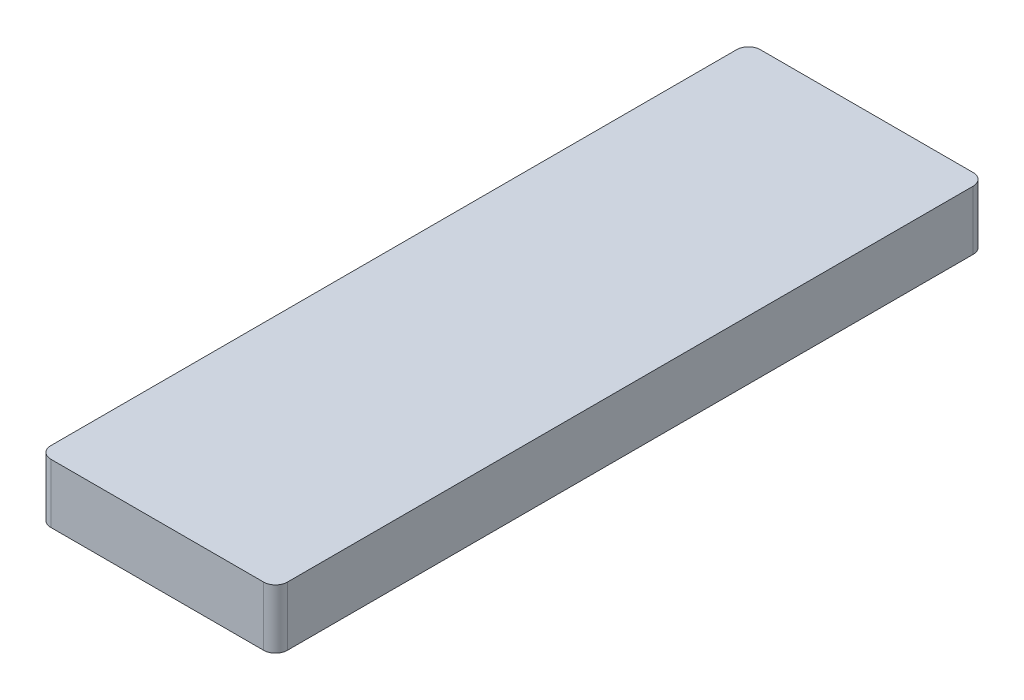
SolidWorks part; units mm, degrees
ref_plane "Front Plane" through (0, 0, 0) normal (0, 0, 1) x (1, 0, 0)
ref_plane "Top Plane" through (0, 0, 0) normal (0, 1, 0) x (1, 0, 0)
ref_plane "Right Plane" through (0, 0, 0) normal (1, 0, 0) x (0, 0, -1)
sketch "Sketch2" plane through (0, 0, 0) normal (0, 1, 0) x (1, 0, 0)
  line L1 (2.54, 0) -> (48.26, 0)
  line L2 (0, 2.54) -> (0, 149.86)
  line L3 (2.54, 152.4) -> (48.26, 152.4)
  line L4 (50.8, 2.54) -> (50.8, 149.86)
  arc A0 (50.8, 2.54) -> (48.26, 0) centre (48.26, 2.54) cw
  arc A1 (50.8, 149.86) -> (48.26, 152.4) centre (48.26, 149.86) ccw
  arc A2 (2.54, 152.4) -> (0, 149.86) centre (2.54, 149.86) ccw
  arc A3 (0, 2.54) -> (2.54, 0) centre (2.54, 2.54) ccw
  point P7 (50.8, 0)
  point P10 (50.8, 152.4)
  point P15 (0, 0)
  dimension "D3" = 2.54
  dimension "D1" = 152.4
  dimension "D2" = 50.8
extrude "Boss-Extrude1" add sketch "Sketch2" along normal blind 12.7
